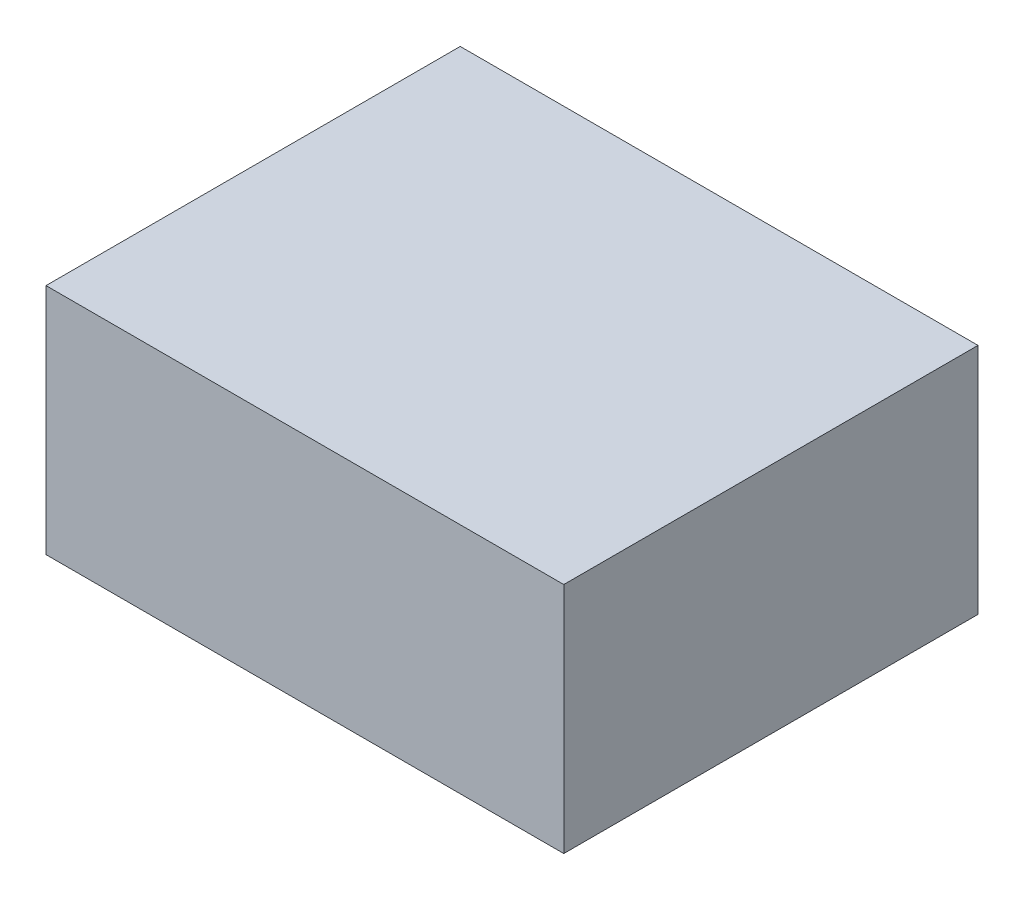
SolidWorks part; units mm, degrees
ref_plane "前视基准面" through (0, 0, 0) normal (0, 0, 1) x (1, 0, 0)
ref_plane "上视基准面" through (0, 0, 0) normal (0, 1, 0) x (1, 0, 0)
ref_plane "右视基准面" through (0, 0, 0) normal (1, 0, 0) x (0, 0, -1)
other "Configuration Table"
sketch "草图1" plane through (0, 0, 0) normal (0, 1, 0) x (1, 0, 0)
  line L1 (0, 0) -> (100, 0)
  line L2 (0, 0) -> (0, -80)
  line L3 (0, -80) -> (100, -80)
  line L4 (100, 0) -> (100, -80)
  dimension "D1" = 100
  dimension "D2" = 80
extrude "凸台-拉伸1" add sketch "草图1" along normal blind 45
